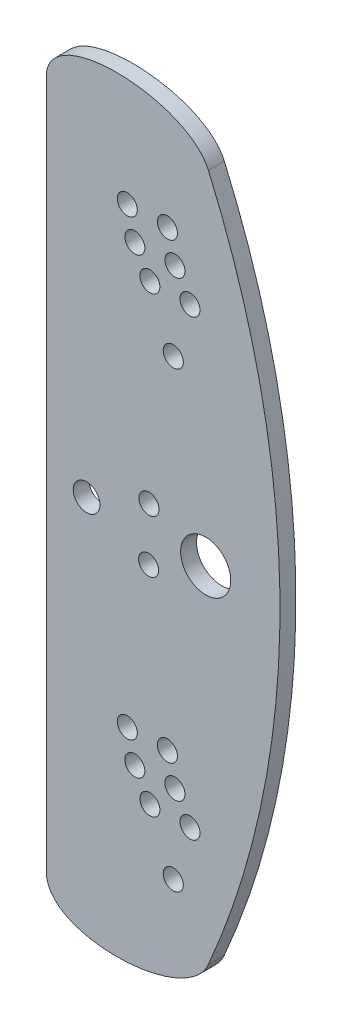
SolidWorks part; units mm, degrees
ref_plane "Front Plane" through (0, 0, 0) normal (0, 0, 1) x (1, 0, 0)
ref_plane "Top Plane" through (0, 0, 0) normal (0, 1, 0) x (1, 0, 0)
ref_plane "Right Plane" through (0, 0, 0) normal (1, 0, 0) x (0, 0, -1)
sketch "Sketch1" plane through (0, 0, 0) normal (0, 0, 1) x (1, 0, 0)
  line L0 (1666.4499, 1807.6633) -> (1666.4499, 984.2921)
  arc A0 (1860.2464, 984.2921) -> (1860.4626, 1807.6633) centre (914.8348, 1396.226) ccw
  circle A1 centre (1811.4021, 1181.9483) radius 12
  circle A2 centre (1820.4021, 1146.9484) radius 12
  circle A3 centre (1838.4021, 1115.6984) radius 12
  circle A4 centre (1772.4022, 1146.9484) radius 12
  circle A5 centre (1790.4022, 1115.6984) radius 12
  circle A6 centre (1763.4022, 1181.9483) radius 12
  circle A7 centre (1818.4016, 1051.9483) radius 12
  circle A8 centre (1811.4021, 1723.9185) radius 12
  circle A9 centre (1820.4021, 1688.9186) radius 12
  circle A10 centre (1838.4021, 1657.6686) radius 12
  circle A11 centre (1772.4022, 1688.9186) radius 12
  circle A12 centre (1790.4022, 1657.6686) radius 12
  circle A13 centre (1763.4022, 1723.9185) radius 12
  circle A14 centre (1818.4016, 1593.9185) radius 12
  circle A15 centre (1788.8617, 1363.1254) radius 12
  circle A16 centre (1789.3361, 1426.6204) radius 12
  circle A17 centre (1857.1926, 1395.9552) radius 29.9999
  circle A18 centre (1714.6902, 1395.9552) radius 15.9995
  spline S0 degree 3 poles (1860.2464, 984.2921) (1834.4426, 925.0708) (1666.4499, 919.6933) (1666.4499, 984.2921) knots 0 0 0 0 7.629784 7.629784 7.629784 7.629784
  spline S1 degree 3 poles (1860.4626, 1807.6633) (1834.6611, 1866.9643) (1666.4499, 1872.3342) (1666.4499, 1807.6633) knots 0 0 0 0 7.638295 7.638295 7.638295 7.638295
extrude "Boss-Extrude1" add sketch "Sketch1" along normal blind 19.05
